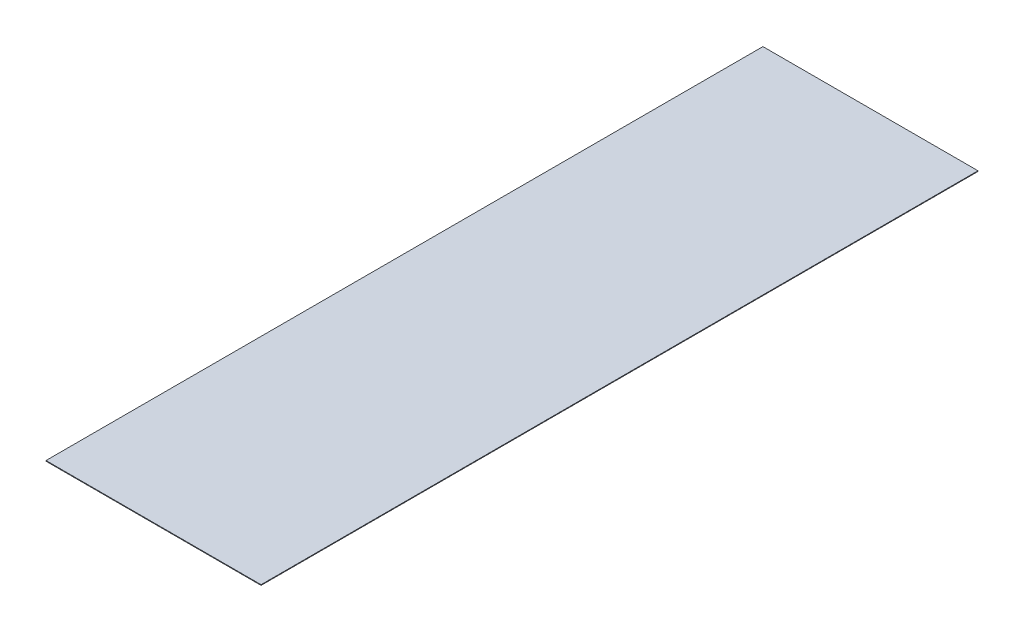
SolidWorks part; units mm, degrees
material "ASTM A36 Acero"
ref_plane "Alzado" through (0, 0, 0) normal (0, 0, 1) x (1, 0, 0)
ref_plane "Planta" through (0, 0, 0) normal (0, 1, 0) x (1, 0, 0)
ref_plane "Vista lateral" through (0, 0, 0) normal (1, 0, 0) x (0, 0, -1)
sketch "Croquis1" plane through (0, 0, 0) normal (0, 1, 0) x (1, 0, 0)
  line L1 (-457.2, -1524) -> (457.2, -1524)
  line L2 (-457.2, -1524) -> (-457.2, 1524)
  line L3 (-457.2, 1524) -> (457.2, 1524)
  line L4 (457.2, -1524) -> (457.2, 1524)
  line L5 (-457.2, -1524) -> (457.2, 1524) construction
  line L6 (-457.2, 1524) -> (457.2, -1524) construction
  point P0 (0, 0)
  dimension "D1" = 3048
  dimension "D2" = 914.4
extrude "Saliente-Extruir1" add sketch "Croquis1" along normal blind 2.7
